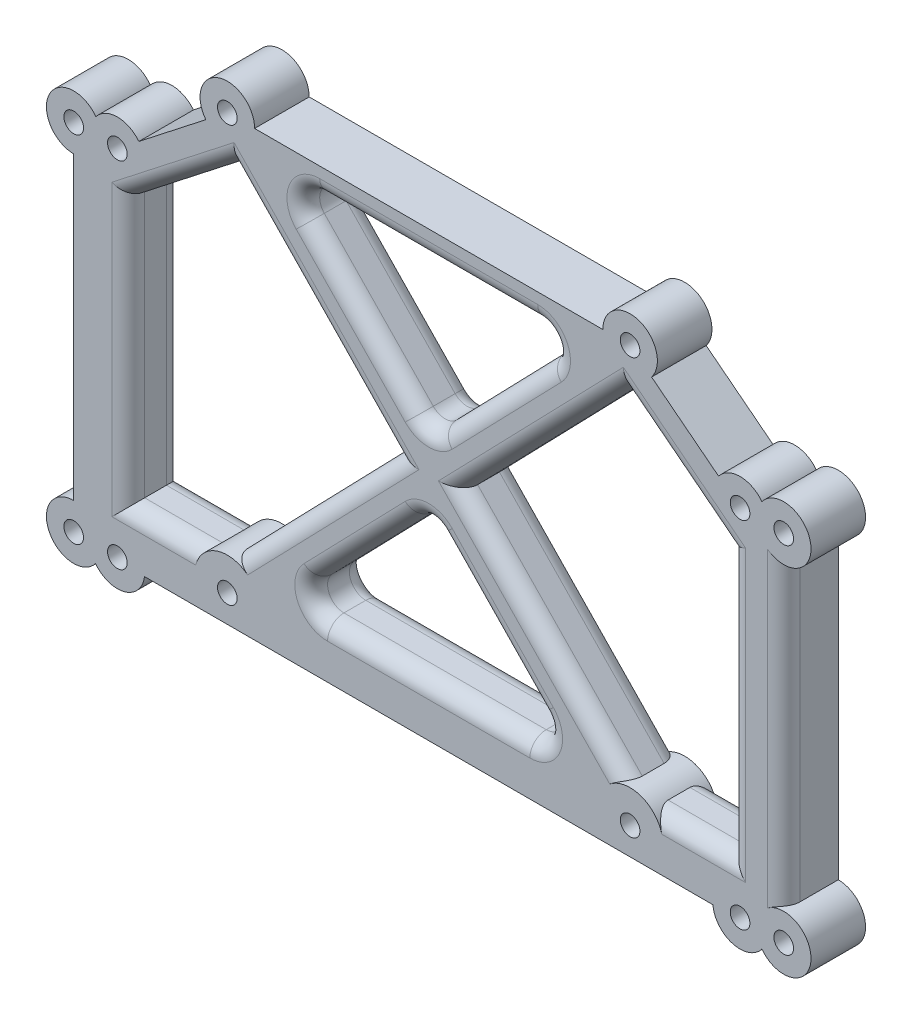
SolidWorks part; units mm, degrees
material "Nylon PA 12"
ref_plane "Front Plane" through (0, 0, 0) normal (0, 0, 1) x (1, 0, 0)
ref_plane "Top Plane" through (0, 0, 0) normal (0, 1, 0) x (1, 0, 0)
ref_plane "Right Plane" through (0, 0, 0) normal (1, 0, 0) x (0, 0, -1)
sketch "Sketch2" plane through (0, 0, 0) normal (0, 0, 1) x (1, 0, 0)
  line L0 (55, 0) -> (-55, 0) construction
  line L1 (86.3487, -50.5747) -> (-86.3487, -50.5747) construction
  line L2 (86.3487, -50.5747) -> (86.3487, 50.5747) construction
  line L3 (86.3487, 50.5747) -> (-86.3487, 50.5747) construction
  line L4 (-86.3487, -50.5747) -> (-86.3487, 50.5747) construction
  line L5 (86.3487, -50.5747) -> (-86.3487, 50.5747) construction
  line L6 (86.3487, 50.5747) -> (-86.3487, -50.5747) construction
  line L7 (0, -55) -> (0, 55) construction
  line L8 (-76.4163, 22.4861) -> (-48.7512, 22.4861) construction
  line L9 (-78.4765, -42.5139) -> (-51.5471, -42.5139) construction
  line L10 (51.414, 22.35) -> (70.6588, 22.35) construction
  line L11 (51.414, -42.65) -> (75.8428, -42.65) construction
  line L12 (-65.0488, 17.4861) -> (-65.05, -37.5139)
  line L13 (-36.9, -43.1) -> (36.9, -43.1)
  line L14 (-36.9, -43.1) -> (-52.0845, -43.1)
  line L15 (36.9, -43.1) -> (52.0703, -43.1)
  line L16 (65.05, 17.35) -> (65.05, -37.65)
  line L18 (-53.1106, 25.4292) -> (-40.8394, 35.0208)
  line L19 (-31.9, 38.1) -> (31.9, 38.1)
  line L20 (-80.0488, 25.4861) -> (-41.05, 25.4861) construction
  line L21 (40.8394, 35.0208) -> (53.1106, 25.4292)
  line L22 (-80.0488, 25.4861) -> (-80.0488, -45.5139) construction
  line L23 (-80.0488, -45.5139) -> (-41.05, -45.5139) construction
  line L24 (-41.05, 25.4861) -> (-41.05, -45.5139) construction
  line L25 (41, 25.35) -> (80.3, 25.35) construction
  line L26 (41, 25.35) -> (41, -45.65) construction
  line L27 (41, -45.65) -> (80.3, -45.65) construction
  line L28 (80.3, 25.35) -> (80.3, -45.65) construction
  circle A4 centre (-36.9, -38.1) radius 1.8
  circle A5 centre (-36.9, 38.1) radius 1.8
  circle A6 centre (36.9, -38.1) radius 1.8
  circle A7 centre (36.9, 38.1) radius 1.8
  circle A8 centre (-65.0488, 22.4861) radius 1.8
  circle A9 centre (-57.05, 22.35) radius 1.8
  circle A10 centre (-65.05, -42.5139) radius 1.8
  circle A12 centre (-57.05, -42.5139) radius 1.8
  circle A13 centre (57.05, 22.35) radius 1.8
  circle A14 centre (65.05, 22.35) radius 1.8
  circle A15 centre (57.05, -42.65) radius 1.8
  circle A16 centre (65.05, -42.65) radius 1.8
  arc A17 (-60.9984, 25.4176) -> (-65.0488, 17.4861) centre (-65.0488, 22.4861) ccw
  arc A18 (-53.1106, 25.4292) -> (-60.9984, 25.4176) centre (-57.05, 22.35) ccw
  arc A19 (-31.9, 38.1) -> (-40.8394, 35.0208) centre (-36.9, 38.1) ccw
  arc A20 (40.8394, 35.0208) -> (31.9, 38.1) centre (36.9, 38.1) ccw
  arc A21 (61.05, 25.35) -> (53.1106, 25.4292) centre (57.05, 22.35) ccw
  arc A22 (65.05, 17.35) -> (61.05, 25.35) centre (65.05, 22.35) ccw
  arc A23 (52.05, -42.65) -> (61.05, -45.65) centre (57.05, -42.65) ccw
  arc A24 (61.05, -45.65) -> (65.05, -37.65) centre (65.05, -42.65) ccw
  circle A25 centre (-36.9, -38.1) radius 5 construction
  arc A26 (-61.05, -45.5139) -> (-52.0845, -43.1) centre (-57.05, -42.5139) ccw
  arc A27 (-65.05, -37.5139) -> (-61.05, -45.5139) centre (-65.05, -42.5139) ccw
  circle A28 centre (36.9, -38.1) radius 5 construction
  point P0 (0, 0)
  dimension "D1" = 65
  dimension "D2" = 38.1
  dimension "D3" = 8
  dimension "D8" = 28.15
  dimension "D9" = 20.15
  dimension "D10" = 8
  dimension "D12" = 65
  dimension "D14" = 3
  dimension "D4" = 73.8
  dimension "D5" = 15.75
  dimension "D6" = 20.15
  dimension "D7" = 73.8
  dimension "D11" = 15.75
  dimension "D13" = 8
  dimension "D15" = 3
  dimension "D16" = 15
  dimension "D17" = 3
  dimension "D18" = 3
  dimension "D19" = 15.25
  dimension "D20" = 16.05
  dimension "D21" = 16
extrude "Boss-Extrude1" add sketch "Sketch2" along normal blind 10
sketch "Sketch3" plane through (0, 0, 10) normal (0, 0, 1) x (1, 0, 0)
  line L0 (-55.0489, 15.0295) -> (-55.0499, -33.5911)
  line L10 (36.9, 38.1) -> (-36.9, -38.1) construction
  line L11 (-36.9, 38.1) -> (36.9, -38.1) construction
  line L12 (-40.8394, 35.0208) -> (-5.9608, -0.992) construction
  line L13 (-31.9, 38.1) -> (0, 5.1626) construction
  line L14 (-55.0499, -33.5911) -> (-40.8585, -33.5911)
  line L15 (40.8585, -33.5911) -> (55.05, -33.5911)
  line L16 (31.9, 38.1) -> (0, 5.1626)
  line L17 (40.8394, 35.0208) -> (5.9608, -0.992)
  line L18 (-25.6116, -33.5911) -> (25.6116, -33.5911)
  line L19 (0, -7.1467) -> (25.6116, -33.5911)
  line L20 (5.9608, -0.992) -> (36.1362, -32.1488)
  line L21 (-5.9608, -0.992) -> (-36.1362, -32.1488)
  line L22 (0, -7.1467) -> (-25.6116, -33.5911)
  line L23 (-55.0489, 15.0295) -> (-35.942, 29.9642)
  line L24 (-27.0575, 33.1) -> (27.0575, 33.1)
  line L25 (35.942, 29.9642) -> (55.05, 15.0286)
  line L26 (-53.1106, 25.4292) -> (-40.8394, 35.0208) construction
  line L27 (-31.9, 38.1) -> (31.9, 38.1) construction
  line L28 (-35.942, 29.9642) -> (-5.9608, -0.992)
  line L29 (-27.0575, 33.1) -> (0, 5.1626)
  line L31 (40.8394, 35.0208) -> (53.1106, 25.4292) construction
  line L32 (55.05, 15.0286) -> (55.05, -33.5911)
  line L33 (65.05, 17.35) -> (65.05, -37.65) construction
  line L34 (-65.0488, 17.4861) -> (-65.05, -37.5139) construction
  arc A0 (40.8394, 35.0208) -> (31.9, 38.1) centre (36.9, 38.1) ccw construction
  arc A1 (-36.1362, -32.1488) -> (-40.8585, -33.5911) centre (-36.9, -38.1) ccw
  arc A2 (40.8585, -33.5911) -> (36.1362, -32.1488) centre (36.9, -38.1) ccw
  dimension "D1" = 5
  dimension "D2" = 7
  dimension "D3" = 7
  dimension "D4" = 10
  dimension "D5" = 10
extrude "Cut-Extrude1" cut sketch "Sketch3" against normal through all contours L28 L23 L0 L14 L21 | L24 L29 L16 | L32 L25 L17 L20 L15 | L19 L22 L18
fillet "Fillet1" radius 3 38 edges at (12.8058, -20.3689, 0) (12.8058, -20.3689, 10) (0, -7.1467, 5) (-12.8058, -20.3689, 0) (-12.8058, -20.3689, 10) (-25.6116, -33.5911, 5) (0, -33.5911, 0) (25.6116, -33.5911, 5) (0, -33.5911, 10) (-21.0485, -16.5704, 0) (-21.0485, -16.5704, 10) (21.0485, -16.5704, 0) (21.0485, -16.5704, 10) (0, 33.1, 0) (0, 33.1, 10) (-27.0575, 33.1, 5) (-13.5287, 19.1313, 0) (-13.5287, 19.1313, 10) (0, 5.1626, 5) (13.5287, 19.1313, 0) (27.0575, 33.1, 5) (13.5287, 19.1313, 10) (-55.0494, -9.2808, 10) (-55.0494, -9.2808, 0) (55.05, -9.2812, 10) (65.05, -10.15, 10) (-45.4954, 22.4968, 0) (-45.4954, 22.4968, 10) (45.496, 22.4964, 10) (45.496, 22.4964, 0) (20.9514, 14.4861, 10) (20.9514, 14.4861, 0) (-20.9514, 14.4861, 0) (-20.9514, 14.4861, 10) (-47.9542, -33.5911, 0) (-47.9542, -33.5911, 10) (47.9543, -33.5911, 0) (47.9543, -33.5911, 10)
fillet "Fillet2" [suppressed] radius 3
